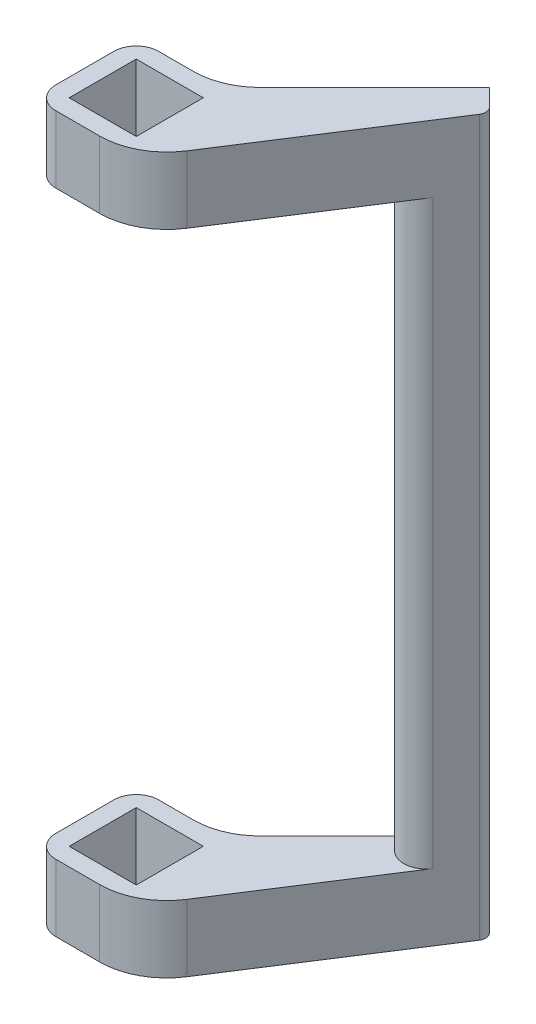
SolidWorks part; units mm, degrees
ref_plane "前视基准面" through (0, 0, 0) normal (0, 0, 1) x (1, 0, 0)
ref_plane "上视基准面" through (0, 0, 0) normal (0, 1, 0) x (1, 0, 0)
ref_plane "右视基准面" through (0, 0, 0) normal (1, 0, 0) x (0, 0, -1)
other "Configuration Table"
sketch "草图1" plane through (0, 0, 0) normal (0, 1, 0) x (1, 0, 0)
  line L0 (-11.5, 11.5) -> (7.5, 11.5)
  line L1 (-7.5, -7.5) -> (7.5, -7.5)
  line L2 (-7.5, -7.5) -> (-7.5, 7.5)
  line L3 (-7.5, 7.5) -> (7.5, 7.5)
  line L4 (7.5, -7.5) -> (7.5, 7.5)
  line L5 (-7.5, -7.5) -> (7.5, 7.5) construction
  line L6 (-7.5, 7.5) -> (7.5, -7.5) construction
  line L8 (-11.5, -11.5) -> (11.5, -11.5)
  line L9 (-11.5, -11.5) -> (-11.5, 11.5)
  line L10 (7.5, 11.5) -> (37.5, 41.5)
  line L12 (37.5, 41.5) -> (42.4497, 36.5503)
  line L13 (-11.5, 11.5) -> (11.5, 11.5) construction
  line L14 (11.5, -11.5) -> (11.5, 11.5) construction
  line L15 (11.5, -11.5) -> (42.4497, 36.5503)
  point P0 (0, 0)
  dimension "D1" = 15
  dimension "D2" = 15
  dimension "D5" = 30
  dimension "D3" = 4
extrude "凸台-拉伸1" add sketch "草图1" along normal blind 160 contours L1 L4 L3 L2 | L10 L12 L15 L8 L9 L0
sketch "草图4" plane through (0, 0, -11.5) normal (0, 0, -1) x (-1, 0, 0)
  line L0 (11.5, 160) -> (-7.5, 160) construction
  line L1 (-62.5488, 145) -> (52.8036, 145)
  line L2 (-62.5488, 145) -> (-62.5488, 15)
  line L3 (-62.5488, 15) -> (52.8036, 15)
  line L4 (52.8036, 145) -> (52.8036, 15)
  line L5 (-7.5, 0) -> (-37.5, 0) construction
  dimension "D1" = 15
  dimension "D2" = 15
extrude "切除-拉伸2" cut sketch "草图4" against normal mid plane 70
fillet "圆角3" radius 5 2 edges at (-11.5, 152.5, -11.5) (-11.5, 152.5, 11.5)
fillet "圆角4" radius 5 2 edges at (-11.5, 7.5, -11.5) (-11.5, 7.5, 11.5)
fillet "圆角6" radius 15 1 edges at (11.5, 152.5, 11.5)
fillet "圆角7" radius 15 1 edges at (11.5, 7.5, 11.5)
fillet "圆角8" radius 15 1 edges at (7.5, 7.5, -11.5)
fillet "圆角9" radius 15 1 edges at (7.5, 152.5, -11.5)
sketch "草图6" plane through (0, 0, 0) normal (0, -1, 0) x (1, 0, 0)
  line L0 (29.7218, -28.065) -> (34.1391, -23.6477)
  line L1 (15.9298, 4.6226) -> (42.4497, -36.5503) construction
  line L2 (34.1391, -23.6477) -> (42.4497, -36.5503)
  line L3 (42.4497, -36.5503) -> (40.3284, -38.6716)
  line L4 (40.3284, -38.6716) -> (29.7218, -28.065)
extrude "凸台-拉伸2" add sketch "草图6" against normal blind 159
fillet "圆角10" radius 5 1 edges at (34.1391, 80, -23.6477)
fillet "圆角11" radius 2 1 edges at (42.4497, 80, -36.5503)
